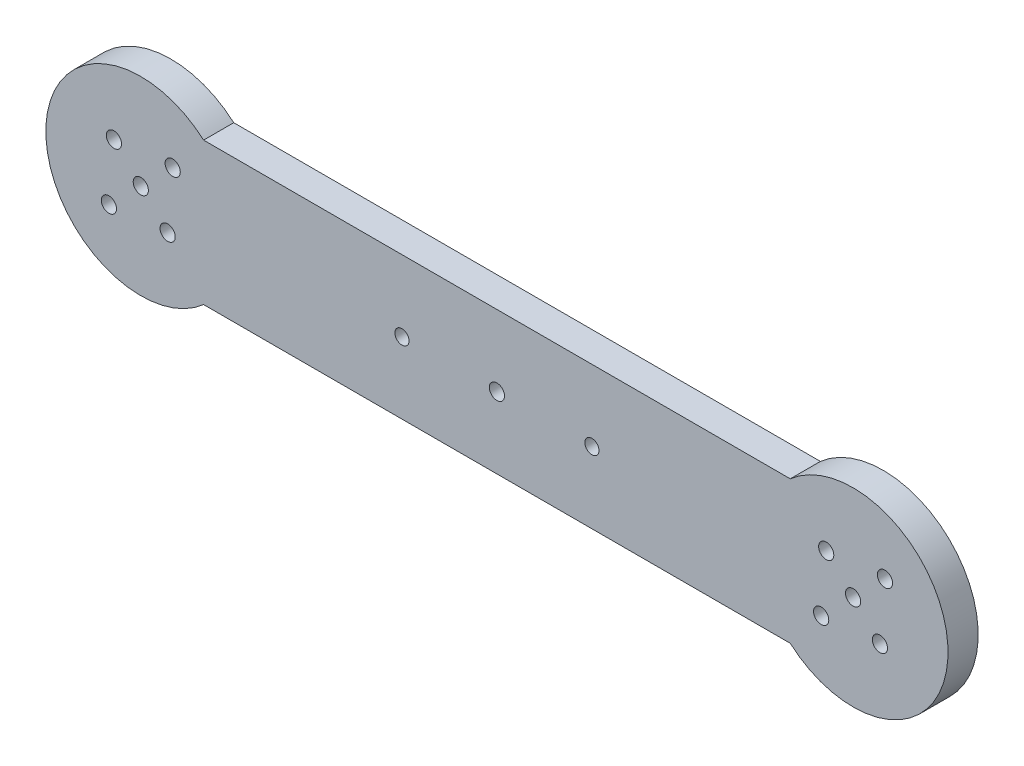
SolidWorks part; units mm, degrees
ref_plane "Front Plane" through (0, 0, 0) normal (0, 0, 1) x (1, 0, 0)
ref_plane "Top Plane" through (0, 0, 0) normal (0, 1, 0) x (1, 0, 0)
ref_plane "Right Plane" through (0, 0, 0) normal (1, 0, 0) x (0, 0, -1)
sketch "Sketch3" plane through (0, 0, 0) normal (0, 0, 1) x (1, 0, 0)
  line L0 (55, 0) -> (-55, 0) construction
  line L2 (61.7712, -15) -> (-61.7712, -15)
  line L4 (61.7712, 15) -> (-61.7712, 15)
  arc A0 (-61.7712, 15) -> (-61.7712, -15) centre (-75, 0) ccw
  arc A1 (61.7712, -15) -> (61.7712, 15) centre (75, 0) ccw
  circle A14 centre (-20, 0) radius 1.5
  circle A15 centre (20, 0) radius 1.5
  point P6 (0, 0)
  dimension "D1" = 40
  dimension "D2" = 40
  dimension "D22" = 3
  dimension "D23" = 3
  dimension "D3" = 150
  dimension "D4" = 75
  dimension "D5" = 30
  dimension "D24" = 20
  dimension "D25" = 20
  dimension "D26" = 15
extrude "Boss-Extrude1" add sketch "Sketch3" along normal blind 6.35
hole_wizard "M3 Clearance Hole1" positions "Sketch4" profile "Sketch5" hole size "M3" standard "ANSI Metric"
sketch "Sketch4" plane through (0, 0, 6.35) normal (0, 0, 1) x (1, 0, 0)
  line L3 (-66.6814, -8.3186) -> (-83.3186, 8.3186) construction
  line L5 (48.7314, 0) -> (-48.7314, 0) construction
  line L6 (-83.3186, -8.3186) -> (-66.6814, 8.3186) construction
  line L7 (-83.3186, 8.3186) -> (-66.6814, -8.3186) construction
  line L8 (-66.6814, 8.3186) -> (-83.3186, -8.3186) construction
  line L9 (0, -23.5157) -> (0, 23.5157) construction
  line L10 (0, -3.4925) -> (0, 3.4925) construction
  line L12 (66.6814, 8.3186) -> (83.3186, -8.3186) construction
  line L13 (83.3186, 8.3186) -> (66.6814, -8.3186) construction
  line L14 (83.3186, -8.3186) -> (66.6814, 8.3186) construction
  line L15 (66.6814, -8.3186) -> (83.3186, 8.3186) construction
  circle A0 centre (-75, 0) radius 9.5 construction
  circle A1 centre (-75, 0) radius 8 construction
  circle A2 centre (75, 0) radius 8 construction
  circle A3 centre (75, 0) radius 9.5 construction
  point P250 (-75, 0)
  point P269 (-81.7175, -6.7175)
  point P271 (-69.3431, -5.6569)
  point P273 (-68.2825, 6.7175)
  point P275 (-80.6569, 5.6569)
  point P308 (0, 0)
  point P318 (81.7175, 6.7175)
  point P319 (69.3431, 5.6569)
  point P320 (68.2825, -6.7175)
  point P321 (80.6569, -5.6569)
  point P322 (75, 0)
  dimension "D1" = 19
  dimension "D2" = 16
  dimension "D3" = 45
  dimension "D4" = 4
sketch "Sketch5" plane through (75, 0, 6.35) normal (1, 0, 0) x (0, -1, 0)
  line L0 (0, 0) -> (0, 8.4614)
  line L1 (0, 8.4614) -> (1.6, 7.5)
  line L2 (1.6, 7.5) -> (1.6, 0)
  line L5 (1.6, 0) -> (0, 0)
  line L10 (0, 8.4614) -> (-1.6, 7.5) construction
  line L11 (0, -6.35) -> (0, 107.95) construction
  dimension "Hole Dia." = 3.2
  dimension "Hole Depth" = 7.5
  dimension "Drill Angle" = 118
